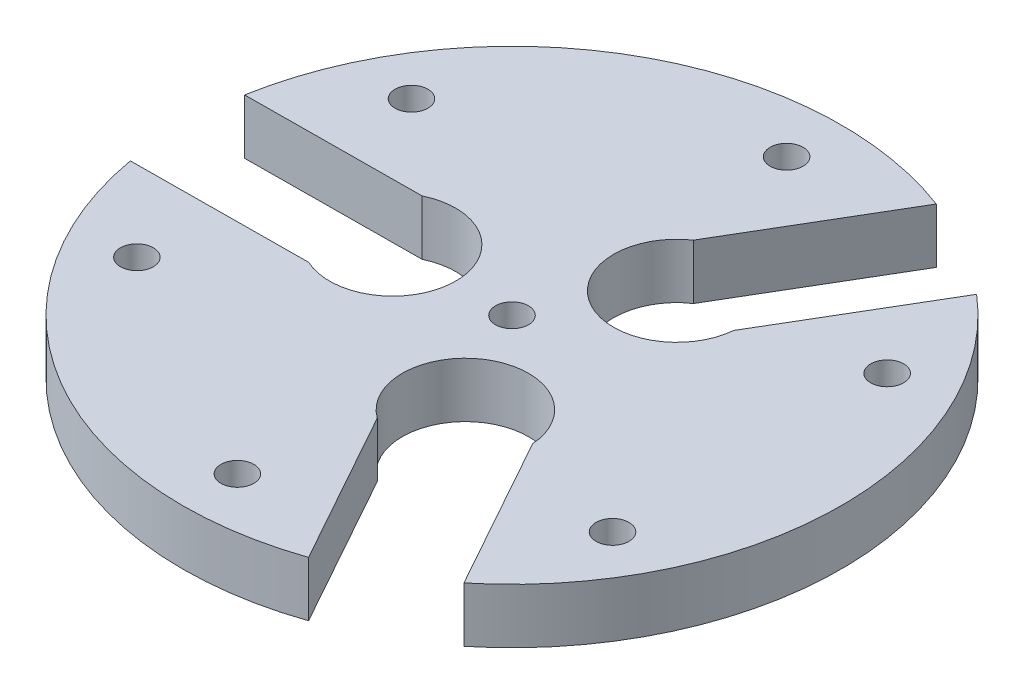
SolidWorks part; units mm, degrees
ref_plane "Front Plane" through (0, 0, 0) normal (0, 0, 1) x (1, 0, 0)
ref_plane "Top Plane" through (0, 0, 0) normal (0, 1, 0) x (1, 0, 0)
ref_plane "Right Plane" through (0, 0, 0) normal (1, 0, 0) x (0, 0, -1)
sketch "Sketch5" plane through (0, 0, 0) normal (0, 1, 0) x (1, 0, 0)
  circle A0 centre (0, 0) radius 30
  point P0 (0, 0)
  dimension "D1" = 60
extrude "Boss-Extrude1" add sketch "Sketch5" along normal blind 5
sketch "Sketch6" plane through (0, 5, 0) normal (0, 1, 0) x (1, 0, 0)
  circle A1 centre (5.5647, 9.4306) radius 5.75
  circle A2 centre (5.3253, -9.5678) radius 5.75
  circle A3 centre (-11.0082, 0.1387) radius 5.75
  dimension "D1" = 11.5
  dimension "D2" = 11.5
  dimension "D3" = 11.5
  dimension "D4" = 19
  dimension "D5" = 19
  dimension "D7" = 19
extrude "Cut-Extrude1" cut sketch "Sketch6" against normal blind 50
sketch "Sketch11" plane through (0, 5, 0) normal (0, 1, 0) x (1, 0, 0)
  circle A0 centre (0, 0) radius 1.5
  dimension "D1" = 3
extrude "Cut-Extrude2" cut sketch "Sketch11" against normal through all
sketch "Sketch13" plane through (0, 5, 0) normal (0, 1, 0) x (1, 0, 0)
  line L0 (0, 0) -> (0, 25) construction
  circle A0 centre (0, 25) radius 1.5
  dimension "D1" = 3
  dimension "D2" = 25
extrude "Cut-Extrude3" cut sketch "Sketch13" against normal blind 10
pattern_circular "CirPattern2" count 6 over 360 about axis through (0, 0, 0) along (0, 1, 0) of "Cut-Extrude3"
sketch "Sketch14" plane through (0, 5, 0) normal (0, 1, 0) x (1, 0, 0)
  line L0 (5.3253, -9.5678) -> (14.5899, -26.2133) construction
  line L1 (9.8689, -7.0389) -> (19.1335, -23.6844)
  line L2 (0.7817, -12.0968) -> (10.0462, -28.7422)
  line L3 (5.5647, 9.4306) -> (15.2456, 25.8374) construction
  line L4 (1.0862, 12.0732) -> (10.7671, 28.48)
  line L5 (10.0431, 6.7881) -> (19.7241, 23.1948)
  line L6 (-11.0082, 0.1387) -> (-30, 0) construction
  line L9 (-10.9702, -5.0612) -> (-29.962, -5.1999)
  line L10 (-11.0462, 5.3385) -> (-30.038, 5.1999)
  circle A0 centre (0, 0) radius 30 construction
  arc A1 (9.8689, -7.0389) -> (0.7817, -12.0968) centre (5.3253, -9.5678) ccw
  arc A2 (10.0462, -28.7422) -> (19.1335, -23.6844) centre (14.5899, -26.2133) ccw
  arc A3 (1.0862, 12.0732) -> (10.0431, 6.7881) centre (5.5647, 9.4306) ccw
  arc A4 (19.7241, 23.1948) -> (10.7671, 28.48) centre (15.2456, 25.8374) ccw
  arc A7 (-10.9702, -5.0612) -> (-11.0462, 5.3385) centre (-11.0082, 0.1387) ccw
  arc A8 (-30.038, 5.1999) -> (-29.962, -5.1999) centre (-30, 0) ccw
  point P5 (9.9576, -17.8906)
  point P13 (10.4051, 17.634)
  point P21 (-20.5041, 0.0693)
  dimension "D1" = 5.2
  dimension "D3" = 5.2
  dimension "D5" = 5.2
  dimension "D2" = 19.05
  dimension "D4" = 19.05
  dimension "D6" = 18.9918
extrude "Cut-Extrude4" cut sketch "Sketch14" against normal blind 10
